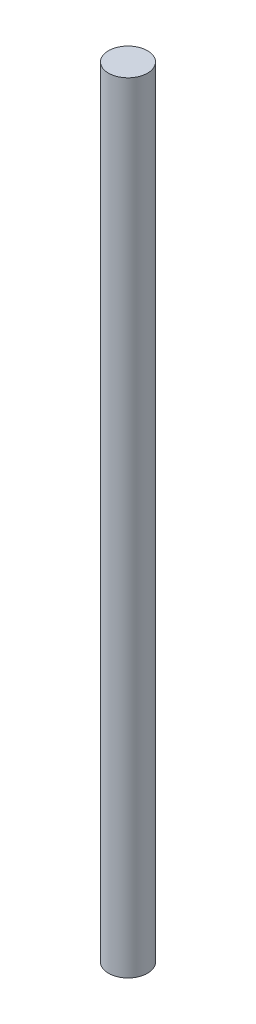
SolidWorks part; units mm, degrees
ref_plane "Front" through (0, 0, 0) normal (0, 0, 1) x (1, 0, 0)
ref_plane "Top" through (0, 0, 0) normal (0, 1, 0) x (1, 0, 0)
ref_plane "Right" through (0, 0, 0) normal (1, 0, 0) x (0, 0, -1)
sketch "Sketch1" plane through (0, 0, 0) normal (0, 1, 0) x (1, 0, 0)
  circle A0 centre (0, 0) radius 3
  dimension "D1" = 6
extrude "Boss-Extrude1" add sketch "Sketch1" along normal blind 120
